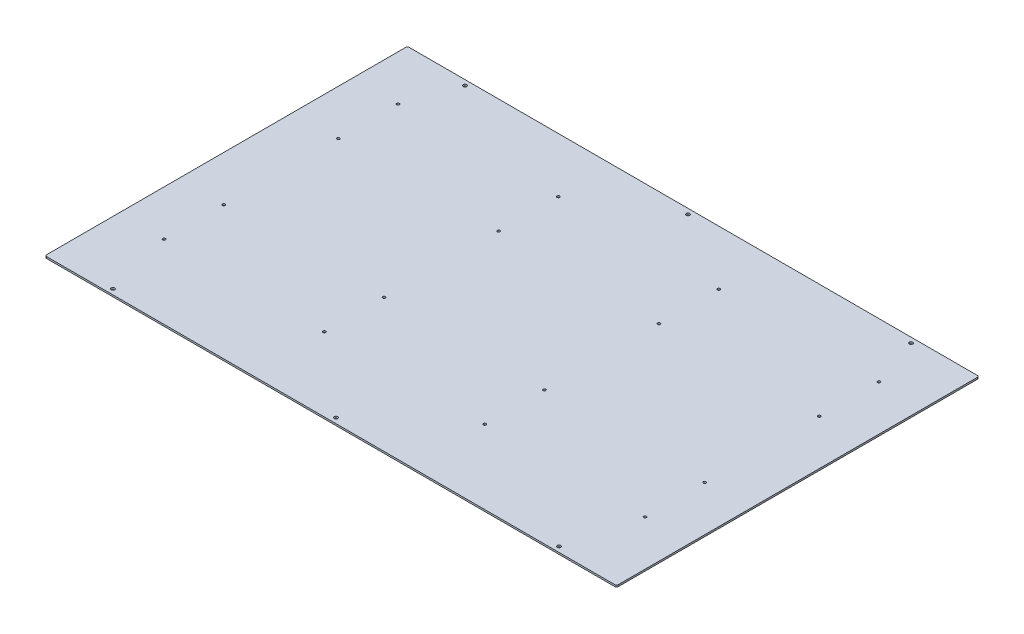
SolidWorks part; units mm, degrees
material "PE High Density"
ref_plane "Front Plane" through (0, 0, 0) normal (0, 0, 1) x (1, 0, 0)
ref_plane "Top Plane" through (0, 0, 0) normal (0, 1, 0) x (1, 0, 0)
ref_plane "Right Plane" through (0, 0, 0) normal (1, 0, 0) x (0, 0, -1)
sketch "Sketch1" plane through (0, 0, 0) normal (0, 1, 0) x (1, 0, 0)
  line L1 (-517.525, -330.2) -> (517.525, -330.2)
  line L2 (-520.7, -327.025) -> (-520.7, 327.025)
  line L3 (-517.525, 330.2) -> (517.525, 330.2)
  line L4 (520.7, -327.025) -> (520.7, 327.025)
  line L5 (-520.7, -330.2) -> (520.7, 330.2) construction
  line L6 (-520.7, 330.2) -> (520.7, -330.2) construction
  arc A0 (-517.525, -330.2) -> (-520.7, -327.025) centre (-517.525, -327.025) cw
  arc A1 (517.525, -330.2) -> (520.7, -327.025) centre (517.525, -327.025) ccw
  arc A2 (517.525, 330.2) -> (520.7, 327.025) centre (517.525, 327.025) cw
  arc A3 (-520.7, 327.025) -> (-517.525, 330.2) centre (-517.525, 327.025) cw
  point P0 (0, 0)
  dimension "D3" = 3.175
  dimension "D1" = 1041.4
  dimension "D2" = 660.4
extrude "Boss-Extrude1" add sketch "Sketch1" along normal blind 3.175
sketch "Sketch2" plane through (0, 3.175, 0) normal (0, 1, 0) x (1, 0, 0)
  line L0 (517.525, 330.2) -> (-517.525, 330.2) construction
  line L1 (-520.7, 327.025) -> (-520.7, -327.025) construction
  line L2 (520.7, -327.025) -> (520.7, 327.025) construction
  line L4 (-517.525, -330.2) -> (517.525, -330.2) construction
  point P0 (-406.4, 320.675)
  point P2 (0, 320.675)
  point P4 (406.4, 320.675)
  point P8 (406.4, -320.675)
  point P10 (0, -320.675)
  point P12 (-406.4, -320.675)
  dimension "D1" = 9.525
  dimension "D2" = 114.3
  dimension "D3" = 406.4
  dimension "D4" = 9.525
  dimension "D5" = 406.4
  dimension "D6" = 114.3
hole_wizard "1/4 (0.25) Diameter Hole1" positions "Sketch3" profile "Sketch4" hole size "1/4" standard "ANSI Inch" end condition through all
sketch "Sketch3" plane through (0, 3.175, 0) normal (0, 1, 0) x (1, 0, 0)
  point P0 (-406.4, 320.675)
  point P6 (0, 320.675)
  point P12 (406.4, 320.675)
  point P24 (406.4, -320.675)
  point P30 (0, -320.675)
  point P36 (-406.4, -320.675)
sketch "Sketch4" plane through (-406.4, 3.175, -320.675) normal (1, 0, 0) x (0, 0, 1)
  line L0 (0, 0) -> (0, 3.175)
  line L1 (0, 3.175) -> (3.175, 3.175)
  line L2 (3.175, 3.175) -> (3.175, 0)
  line L5 (3.175, 0) -> (0, 0)
  line L11 (0, -6.35) -> (0, 107.95) construction
  dimension "Thru Hole Dia." = 6.35
  dimension "Thru Hole Depth" = 3.175
sketch "Sketch5" plane through (0, 3.175, 0) normal (0, 1, 0) x (1, 0, 0)
  point P0 (-438.15, 230.4683)
  point P1 (-438.15, 121.7563)
  point P5 (-146.05, 230.4683)
  point P7 (-146.05, 121.7563)
  point P17 (146.05, 230.4683)
  point P19 (146.05, 121.7563)
  point P23 (438.15, 230.4683)
  point P25 (438.15, 121.7563)
  point P39 (438.15, -87.0317)
  point P43 (438.15, -195.7437)
  point P45 (146.05, -195.7437)
  point P47 (146.05, -87.0317)
  point P51 (-146.05, -87.0317)
  point P55 (-146.05, -195.7437)
  point P63 (-438.15, -87.0317)
  point P65 (-438.15, -195.7437)
  dimension "D1" = 108.712
  dimension "D2" = 108.712
  dimension "D3" = 292.1
  dimension "D4" = 292.1
  dimension "D5" = 146.05
  dimension "D6" = 146.05
  dimension "D7" = 121.7563
  dimension "D8" = 87.0317
hole_wizard "#10 (0.1935) Diameter Hole1" positions "3DSketch1" profile "Sketch6" hole size "#10" standard "ANSI Inch" end condition through all
sketch3d "3DSketch1"
  point P0 (-438.15, 3.175, -230.4683)
  point P6 (-438.15, 3.175, -121.7563)
  point P9 (-146.05, 3.175, -121.7563)
  point P12 (-146.05, 3.175, -230.4683)
  point P24 (146.05, 3.175, -121.7563)
  point P27 (146.05, 3.175, -230.4683)
  point P36 (438.15, 3.175, -230.4683)
  point P39 (438.15, 3.175, -121.7563)
  point P51 (-438.15, 3.175, 87.0317)
  point P54 (-438.15, 3.175, 195.7437)
  point P66 (-146.05, 3.175, 195.7437)
  point P69 (-146.05, 3.175, 87.0317)
  point P75 (146.05, 3.175, 87.0317)
  point P81 (146.05, 3.175, 195.7437)
  point P87 (438.15, 3.175, 87.0317)
  point P90 (438.15, 3.175, 195.7437)
sketch "Sketch6" plane through (-438.15, 3.175, -230.4683) normal (1, 0, 0) x (0, 0, 1)
  line L0 (0, 0) -> (0, 3.175)
  line L1 (0, 3.175) -> (2.4574, 3.175)
  line L2 (2.4574, 3.175) -> (2.4574, 0)
  line L5 (2.4574, 0) -> (0, 0)
  line L11 (0, -6.35) -> (0, 107.95) construction
  dimension "Thru Hole Dia." = 4.9149
  dimension "Thru Hole Depth" = 3.175
